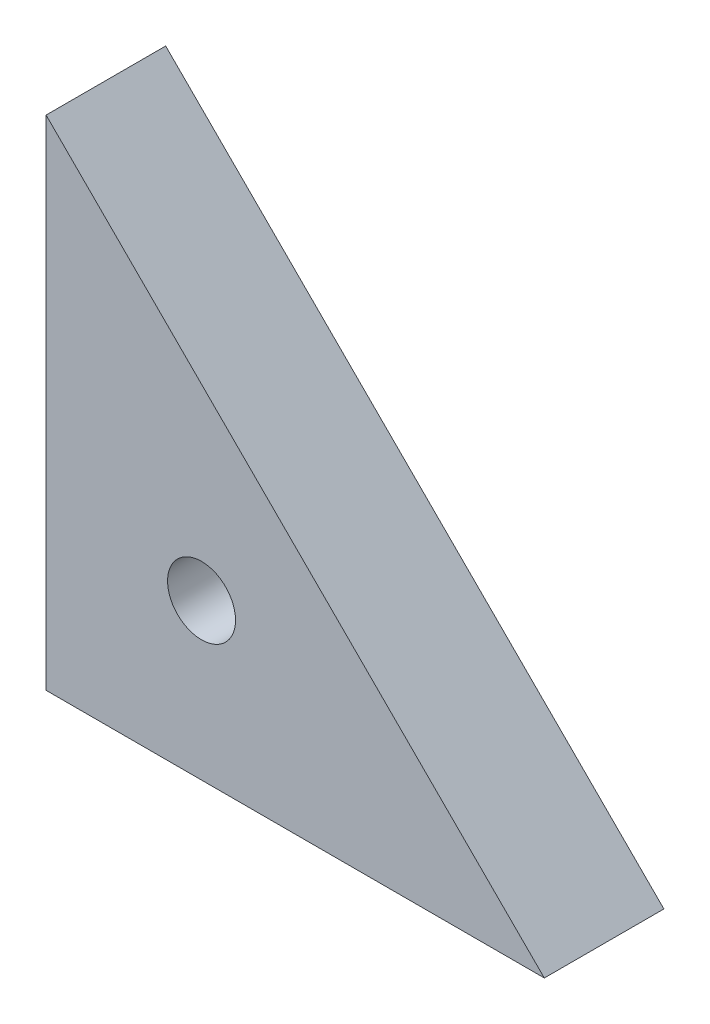
SolidWorks part; units mm, degrees
ref_plane "Front Plane" through (0, 0, 0) normal (0, 0, 1) x (1, 0, 0)
ref_plane "Top Plane" through (0, 0, 0) normal (0, 1, 0) x (1, 0, 0)
ref_plane "Right Plane" through (0, 0, 0) normal (1, 0, 0) x (0, 0, -1)
sketch "Sketch1" plane through (0, 0, 0) normal (0, 0, 1) x (1, 0, 0)
  line L0 (0, 0) -> (0, 25)
  line L1 (0, 25) -> (25, 0)
  line L2 (25, 0) -> (0, 0)
  circle A0 centre (7.8, 7.8) radius 1.705
  dimension "D3" = 3.41
  dimension "D4" = 7.8
  dimension "D5" = 7.8
  dimension "D1" = 25
  dimension "D2" = 25
extrude "Boss-Extrude1" add sketch "Sketch1" along normal blind 6
